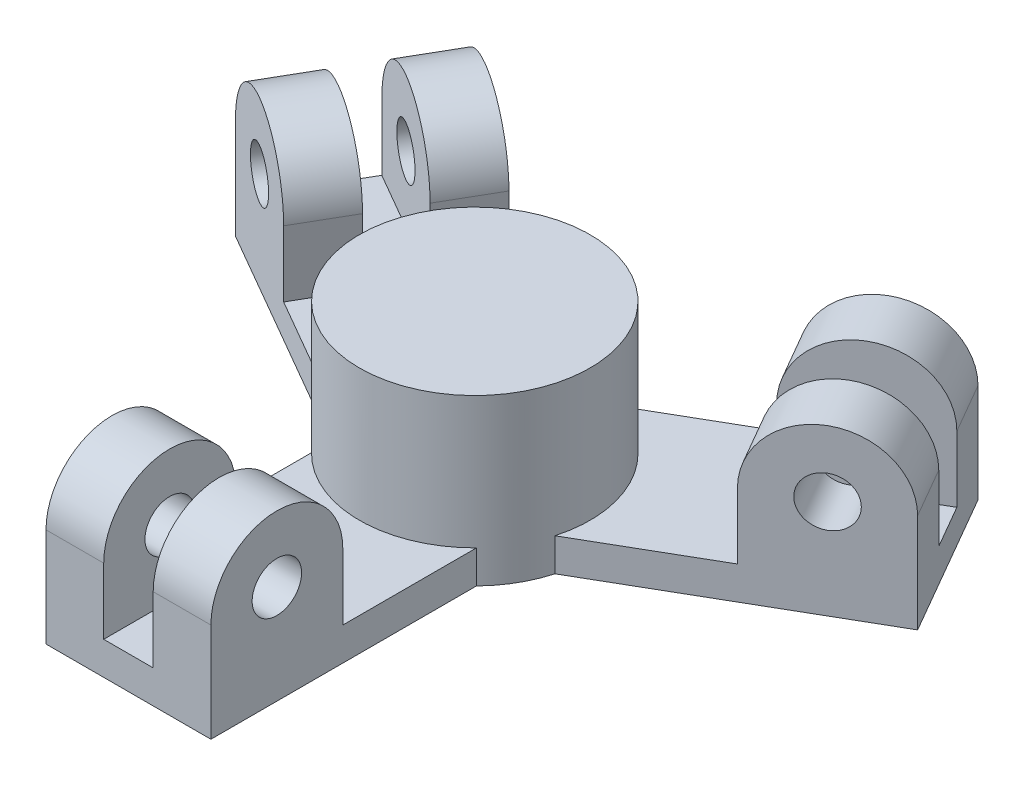
SolidWorks part; units mm, degrees
ref_plane "Front" through (0, 0, 0) normal (0, 0, 1) x (1, 0, 0)
ref_plane "Top" through (0, 0, 0) normal (0, 1, 0) x (1, 0, 0)
ref_plane "Right" through (0, 0, 0) normal (1, 0, 0) x (0, 0, -1)
sketch "Sketch1" plane through (0, 0, 0) normal (0, 1, 0) x (1, 0, 0)
  circle A0 centre (0, 0) radius 7
  dimension "D1" = 14
extrude "Boss-Extrude1" add sketch "Sketch1" along normal blind 10
sketch "Sketch2" plane through (0, 0, 0) normal (0, -1, 0) x (1, 0, 0)
  line L1 (-5, 21) -> (5, 21)
  line L2 (-5, 21) -> (-5, 0)
  line L3 (-5, 0) -> (5, 0)
  line L4 (5, 21) -> (5, 0)
  circle A1 centre (0, 0) radius 7 construction
  dimension "D1" = 14
  dimension "D2" = 10
extrude "Boss-Extrude2" add sketch "Sketch2" against normal blind 2
sketch "Sketch3" plane through (0, 0, 21) normal (0, 0, 1) x (1, 0, 0)
  line L1 (-5, 2) -> (-1.5, 2)
  line L2 (-5, 2) -> (-5, 10)
  line L3 (-5, 10) -> (-1.5, 10)
  line L4 (-1.5, 2) -> (-1.5, 10)
  line L7 (5, 2) -> (1.5, 2)
  line L8 (5, 2) -> (5, 10)
  line L9 (5, 10) -> (1.5, 10)
  line L10 (1.5, 2) -> (1.5, 10)
  dimension "D1" = 3
  dimension "D2" = 8
extrude "Boss-Extrude3" add sketch "Sketch3" against normal blind 8
sketch "Sketch4" plane through (5, 0, 0) normal (1, 0, 0) x (0, 0, -1)
  line L0 (-13, 2) -> (-13, 10) construction
  line L1 (-21, 10) -> (-21, 0) construction
  line L2 (-21, 6) -> (-21, 11)
  line L3 (-21, 11) -> (-13, 11)
  line L4 (-13, 11) -> (-13, 6)
  line L5 (-13, 10) -> (-21, 10) construction
  arc A0 (-13, 6) -> (-21, 6) centre (-17, 6) ccw
  dimension "D1" = 1
extrude "Cut-Extrude1" cut sketch "Sketch4" against normal through all
sketch "Sketch5" plane through (5, 0, 0) normal (1, 0, 0) x (0, 0, -1)
  circle A0 centre (-17, 6) radius 1.5
  dimension "D1" = 3
extrude "Cut-Extrude2" cut sketch "Sketch5" against normal through all
pattern_circular "CirPattern1" count 3 every 120 about axis through (0, 0, 0) along (0, 1, 0) of "Boss-Extrude2", "Boss-Extrude3", "Cut-Extrude1", "Cut-Extrude2"
